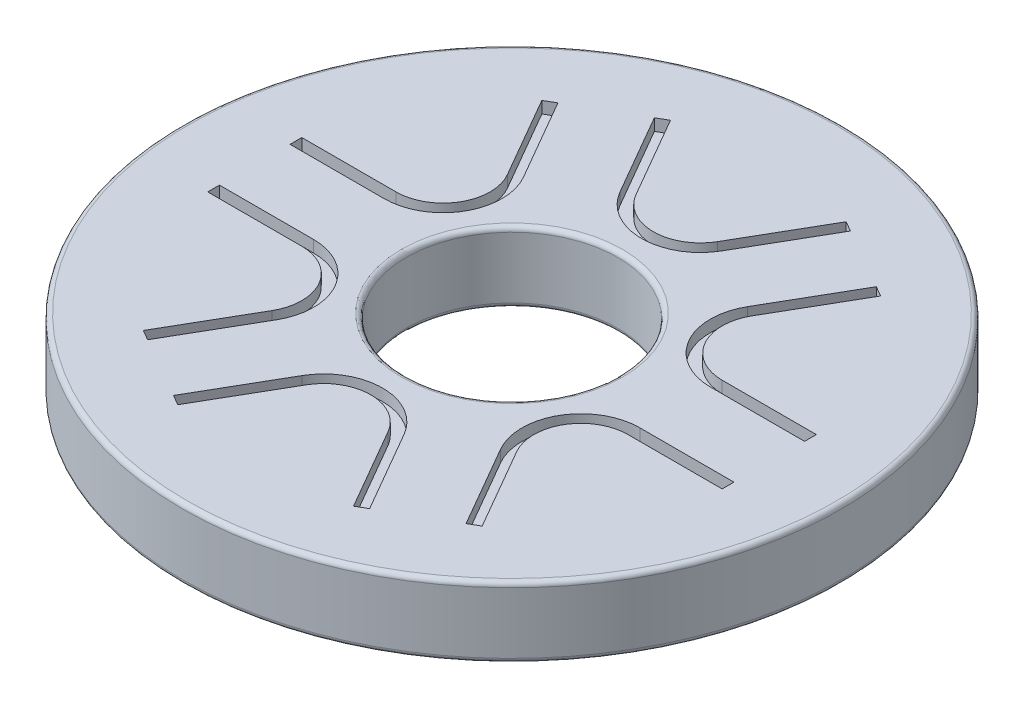
SolidWorks part; units mm, degrees
ref_plane "Front Plane" through (0, 0, 0) normal (0, 0, 1) x (1, 0, 0)
ref_plane "Top Plane" through (0, 0, 0) normal (0, 1, 0) x (1, 0, 0)
ref_plane "Right Plane" through (0, 0, 0) normal (1, 0, 0) x (0, 0, -1)
sketch "Sketch1" plane through (0, 0, 0) normal (0, 1, 0) x (1, 0, 0)
  circle A0 centre (0, 0) radius 4.5
  circle A1 centre (0, 0) radius 14
  dimension "D1" = 28
  dimension "D2" = 9
extrude "Boss-Extrude1" add sketch "Sketch1" along normal blind 3
sketch "Sketch2" plane through (0, 3, 0) normal (0, 1, 0) x (1, 0, 0)
  line L0 (-2.1651, 6.75) -> (-4.1651, 10.2141)
  line L1 (2.1651, 6.75) -> (4.1651, 10.2141)
  line L2 (0, 0) -> (0, 8) construction
  line L3 (1.7321, 7) -> (3.7321, 10.4641)
  line L4 (-1.7321, 7) -> (-3.7321, 10.4641)
  line L5 (-3.7321, 10.4641) -> (-4.1651, 10.2141)
  line L6 (3.7321, 10.4641) -> (4.1651, 10.2141)
  line L7 (5.1962, 5) -> (7.1962, 8.4641)
  line L8 (4.7631, 5.25) -> (6.7631, 8.7141)
  line L9 (6.9282, 2) -> (10.9282, 2)
  line L10 (6.9282, 1.5) -> (10.9282, 1.5)
  line L11 (10.9282, 2) -> (10.9282, 1.5)
  line L12 (7.1962, 8.4641) -> (6.7631, 8.7141)
  line L13 (6.9282, -2) -> (10.9282, -2)
  line L14 (6.9282, -1.5) -> (10.9282, -1.5)
  line L15 (5.1962, -5) -> (7.1962, -8.4641)
  line L16 (4.7631, -5.25) -> (6.7631, -8.7141)
  line L17 (7.1962, -8.4641) -> (6.7631, -8.7141)
  line L18 (10.9282, -2) -> (10.9282, -1.5)
  line L19 (1.7321, -7) -> (3.7321, -10.4641)
  line L20 (2.1651, -6.75) -> (4.1651, -10.2141)
  line L21 (-1.7321, -7) -> (-3.7321, -10.4641)
  line L22 (-2.1651, -6.75) -> (-4.1651, -10.2141)
  line L23 (-3.7321, -10.4641) -> (-4.1651, -10.2141)
  line L24 (3.7321, -10.4641) -> (4.1651, -10.2141)
  line L25 (-5.1962, -5) -> (-7.1962, -8.4641)
  line L26 (-4.7631, -5.25) -> (-6.7631, -8.7141)
  line L27 (-6.9282, -2) -> (-10.9282, -2)
  line L28 (-6.9282, -1.5) -> (-10.9282, -1.5)
  line L29 (-10.9282, -2) -> (-10.9282, -1.5)
  line L30 (-7.1962, -8.4641) -> (-6.7631, -8.7141)
  line L31 (-6.9282, 2) -> (-10.9282, 2)
  line L32 (-6.9282, 1.5) -> (-10.9282, 1.5)
  line L33 (-5.1962, 5) -> (-7.1962, 8.4641)
  line L34 (-4.7631, 5.25) -> (-6.7631, 8.7141)
  line L35 (-7.1962, 8.4641) -> (-6.7631, 8.7141)
  line L36 (-10.9282, 2) -> (-10.9282, 1.5)
  arc A0 (-2.1651, 6.75) -> (2.1651, 6.75) centre (0, 8) ccw
  arc A1 (-1.7321, 7) -> (1.7321, 7) centre (0, 8) ccw
  arc A2 (4.7631, 5.25) -> (6.9282, 1.5) centre (6.9282, 4) ccw
  arc A3 (5.1962, 5) -> (6.9282, 2) centre (6.9282, 4) ccw
  arc A4 (6.9282, -1.5) -> (4.7631, -5.25) centre (6.9282, -4) ccw
  arc A5 (6.9282, -2) -> (5.1962, -5) centre (6.9282, -4) ccw
  arc A6 (2.1651, -6.75) -> (-2.1651, -6.75) centre (0, -8) ccw
  arc A7 (1.7321, -7) -> (-1.7321, -7) centre (0, -8) ccw
  arc A8 (-4.7631, -5.25) -> (-6.9282, -1.5) centre (-6.9282, -4) ccw
  arc A9 (-5.1962, -5) -> (-6.9282, -2) centre (-6.9282, -4) ccw
  arc A10 (-6.9282, 1.5) -> (-4.7631, 5.25) centre (-6.9282, 4) ccw
  arc A11 (-6.9282, 2) -> (-5.1962, 5) centre (-6.9282, 4) ccw
  point P64 (0, 0)
  dimension "D1" = 5
  dimension "D2" = 8
  dimension "D3" = 30
  dimension "D4" = 30
  dimension "D5" = 4
  dimension "D6" = 4
  dimension "D8" = 6
  dimension "D7" = 0.5
extrude "Cut-Extrude1" cut sketch "Sketch2" against normal blind 0.5
fillet "Fillet1" radius 0.2 4 edges at (0, 0, 14) (0, 3, 14) (0, 0, 4.5) (0, 3, 4.5)
